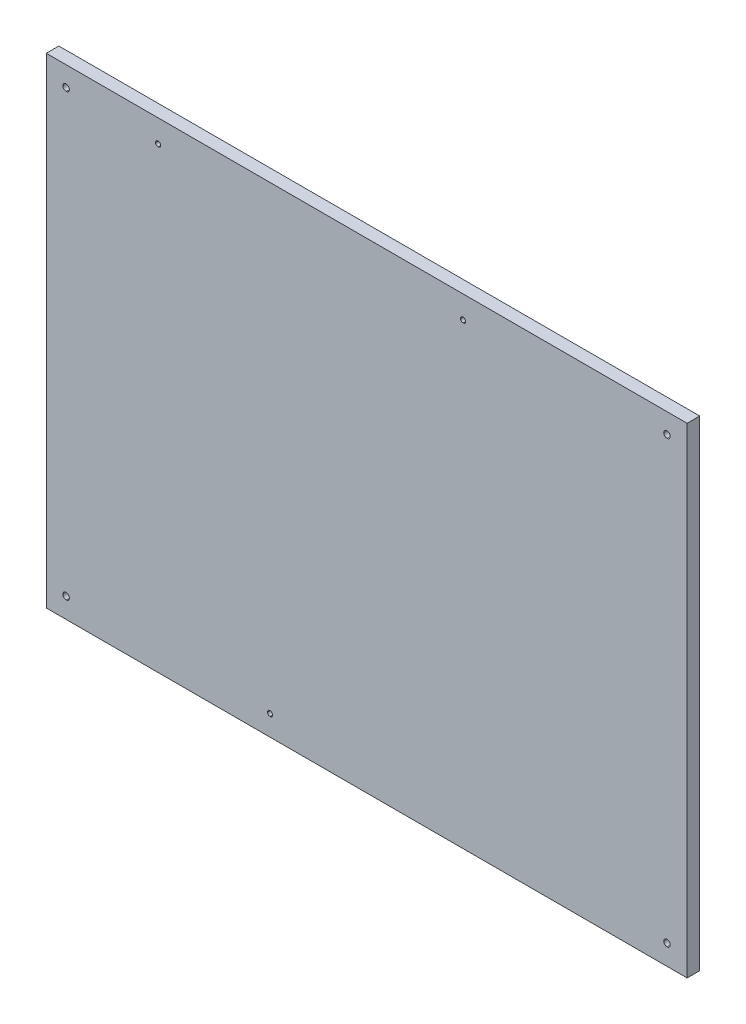
SolidWorks part; units mm, degrees
ref_plane "Front Plane" through (0, 0, 0) normal (0, 0, 1) x (1, 0, 0)
ref_plane "Top Plane" through (0, 0, 0) normal (0, 1, 0) x (1, 0, 0)
ref_plane "Right Plane" through (0, 0, 0) normal (1, 0, 0) x (0, 0, -1)
sketch "Model" plane through (0, 0, 0) normal (0, 0, 1) x (1, 0, 0)
  line L202 (85.3017, 123.303) -> (87.3337, 123.303)
  line L203 (87.3337, 123.303) -> (87.3337, 125.335)
  line L204 (87.3337, 125.335) -> (85.3017, 125.335)
  line L205 (85.3017, 125.335) -> (85.3017, 123.303)
  line L225 (58.3777, 121.779) -> (138.3453, 121.779)
  line L226 (138.3453, 121.779) -> (138.3453, 181.723)
  line L227 (138.3453, 181.723) -> (58.3777, 181.723)
  line L228 (58.3777, 181.723) -> (58.3777, 121.779)
  line L1737 (85.0477, 123.049) -> (110.4053, 123.049)
  line L1738 (110.4053, 123.049) -> (110.4053, 125.589)
  line L1739 (110.4053, 125.589) -> (85.0477, 125.589)
  line L1740 (85.0477, 125.589) -> (85.0477, 123.049)
  line L1741 (87.5877, 125.589) -> (87.5877, 123.049)
  line L1742 (96.9857, 126.3087) -> (96.9857, 126.224)
  line L1743 (96.9857, 126.224) -> (97.0703, 126.097)
  line L1744 (97.0703, 126.097) -> (97.4513, 126.097)
  line L1745 (97.4513, 126.097) -> (97.536, 126.224)
  line L1746 (97.536, 126.224) -> (97.536, 126.732)
  line L1747 (98.298, 126.5204) -> (98.2133, 126.4357)
  line L1748 (98.2133, 126.4357) -> (97.917, 126.4357)
  line L1749 (97.917, 126.4357) -> (97.8323, 126.5204)
  line L1750 (97.8323, 126.5204) -> (97.8323, 126.605)
  line L1751 (97.8323, 126.605) -> (97.917, 126.732)
  line L1752 (97.917, 126.732) -> (98.2133, 126.732)
  line L1753 (98.2133, 126.732) -> (98.298, 126.605)
  line L1754 (98.298, 126.605) -> (98.298, 126.224)
  line L1755 (98.298, 126.224) -> (98.2133, 126.097)
  line L1756 (98.2133, 126.097) -> (97.917, 126.097)
  line L1889 (67.2677, 178.8444) -> (67.564, 178.8444)
  line L1890 (67.564, 178.8444) -> (67.564, 178.548)
  line L1891 (67.564, 178.548) -> (66.929, 178.548)
  line L1892 (66.929, 178.548) -> (66.6327, 178.8444)
  line L1893 (66.6327, 178.8444) -> (66.6327, 179.1407)
  line L1894 (66.6327, 179.1407) -> (66.929, 179.437)
  line L1895 (66.929, 179.437) -> (67.3947, 179.437)
  line L1896 (67.3947, 179.437) -> (67.564, 179.31)
  line L1897 (67.9027, 178.548) -> (67.9027, 179.437)
  line L1898 (67.9027, 179.437) -> (68.834, 178.548)
  line L1899 (68.834, 178.548) -> (68.834, 179.437)
  line L1900 (69.1727, 178.548) -> (69.1727, 179.437)
  line L1901 (69.1727, 179.437) -> (69.8077, 179.437)
  line L1902 (69.8077, 179.437) -> (70.104, 179.1407)
  line L1903 (70.104, 179.1407) -> (70.104, 178.8444)
  line L1904 (70.104, 178.8444) -> (69.8077, 178.548)
  line L1905 (69.8077, 178.548) -> (69.1727, 178.548)
  line L1906 (74.549, 181.0457) -> (74.8877, 181.342)
  line L1907 (74.8877, 181.342) -> (74.8877, 180.453)
  line L1908 (76.9197, 181.215) -> (77.089, 181.342)
  line L1909 (77.089, 181.342) -> (77.5547, 181.342)
  line L1910 (77.5547, 181.342) -> (77.724, 181.215)
  line L1911 (77.724, 181.215) -> (77.724, 181.0457)
  line L1912 (77.724, 181.0457) -> (77.5547, 180.9187)
  line L1913 (77.5547, 180.9187) -> (77.089, 180.9187)
  line L1914 (77.089, 180.9187) -> (76.9197, 180.7494)
  line L1915 (76.9197, 180.7494) -> (76.9197, 180.453)
  line L1916 (76.9197, 180.453) -> (77.724, 180.453)
  line L1917 (79.4597, 181.215) -> (79.629, 181.342)
  line L1918 (79.629, 181.342) -> (80.0947, 181.342)
  line L1919 (80.0947, 181.342) -> (80.264, 181.215)
  line L1920 (80.264, 181.215) -> (80.264, 181.0457)
  line L1921 (80.264, 181.0457) -> (80.0947, 180.9187)
  line L1922 (80.0947, 180.9187) -> (80.264, 180.7494)
  line L1923 (80.264, 180.7494) -> (80.264, 180.58)
  line L1924 (80.264, 180.58) -> (80.0947, 180.453)
  line L1925 (80.0947, 180.453) -> (79.629, 180.453)
  line L1926 (79.629, 180.453) -> (79.4597, 180.58)
  line L1927 (79.7983, 180.9187) -> (80.0947, 180.9187)
  line L1928 (82.804, 180.7494) -> (81.8727, 180.7494)
  line L1929 (81.8727, 180.7494) -> (82.5077, 181.342)
  line L1930 (82.5077, 181.342) -> (82.5077, 180.453)
  line L1931 (113.2417, 181.342) -> (112.4373, 181.342)
  line L1932 (112.4373, 181.342) -> (112.4373, 181.0457)
  line L1933 (112.4373, 181.0457) -> (113.0723, 181.0457)
  line L1934 (113.0723, 181.0457) -> (113.2417, 180.9187)
  line L1935 (113.2417, 180.9187) -> (113.2417, 180.58)
  line L1936 (113.2417, 180.58) -> (113.0723, 180.453)
  line L1937 (113.0723, 180.453) -> (112.6067, 180.453)
  line L1938 (112.6067, 180.453) -> (112.4373, 180.58)
  line L1939 (115.7817, 181.215) -> (115.6123, 181.342)
  line L1940 (115.6123, 181.342) -> (115.1467, 181.342)
  line L1941 (115.1467, 181.342) -> (114.9773, 181.215)
  line L1942 (114.9773, 181.215) -> (114.9773, 180.58)
  line L1943 (114.9773, 180.58) -> (115.1467, 180.453)
  line L1944 (115.1467, 180.453) -> (115.6123, 180.453)
  line L1945 (115.6123, 180.453) -> (115.7817, 180.58)
  line L1946 (115.7817, 180.58) -> (115.7817, 180.7494)
  line L1947 (115.7817, 180.7494) -> (115.6123, 180.9187)
  line L1948 (115.6123, 180.9187) -> (114.9773, 180.9187)
  line L1949 (117.5173, 181.342) -> (118.3217, 181.342)
  line L1950 (118.3217, 181.342) -> (118.3217, 181.215)
  line L1951 (118.3217, 181.215) -> (117.5173, 180.453)
  line L1952 (120.2267, 180.9187) -> (120.0573, 181.0457)
  line L1953 (120.0573, 181.0457) -> (120.0573, 181.215)
  line L1954 (120.0573, 181.215) -> (120.2267, 181.342)
  line L1955 (120.2267, 181.342) -> (120.6923, 181.342)
  line L1956 (120.6923, 181.342) -> (120.8617, 181.215)
  line L1957 (120.8617, 181.215) -> (120.8617, 181.0457)
  line L1958 (120.8617, 181.0457) -> (120.6923, 180.9187)
  line L1959 (120.6923, 180.9187) -> (120.2267, 180.9187)
  line L1960 (120.2267, 180.9187) -> (120.0573, 180.7494)
  line L1961 (120.0573, 180.7494) -> (120.0573, 180.58)
  line L1962 (120.0573, 180.58) -> (120.2267, 180.453)
  line L1963 (120.2267, 180.453) -> (120.6923, 180.453)
  line L1964 (120.6923, 180.453) -> (120.8617, 180.58)
  line L1965 (120.8617, 180.58) -> (120.8617, 180.7494)
  line L1966 (120.8617, 180.7494) -> (120.6923, 180.9187)
  line L1967 (105.3677, 178.8444) -> (105.664, 178.8444)
  line L1968 (105.664, 178.8444) -> (105.664, 178.548)
  line L1969 (105.664, 178.548) -> (105.029, 178.548)
  line L1970 (105.029, 178.548) -> (104.7327, 178.8444)
  line L1971 (104.7327, 178.8444) -> (104.7327, 179.1407)
  line L1972 (104.7327, 179.1407) -> (105.029, 179.437)
  line L1973 (105.029, 179.437) -> (105.4947, 179.437)
  line L1974 (105.4947, 179.437) -> (105.664, 179.31)
  line L1975 (106.0027, 178.548) -> (106.0027, 179.437)
  line L1976 (106.0027, 179.437) -> (106.934, 178.548)
  line L1977 (106.934, 178.548) -> (106.934, 179.437)
  line L1978 (107.2727, 178.548) -> (107.2727, 179.437)
  line L1979 (107.2727, 179.437) -> (107.9077, 179.437)
  line L1980 (107.9077, 179.437) -> (108.204, 179.1407)
  line L1981 (108.204, 179.1407) -> (108.204, 178.8444)
  line L1982 (108.204, 178.8444) -> (107.9077, 178.548)
  line L1983 (107.9077, 178.548) -> (107.2727, 178.548)
  line L1984 (80.6027, 124.446) -> (81.534, 124.446)
  line L1985 (81.0683, 124.7424) -> (81.0683, 124.1074)
  line L1986 (82.169, 124.446) -> (81.9997, 124.573)
  line L1987 (81.9997, 124.573) -> (81.9997, 124.7424)
  line L1988 (81.9997, 124.7424) -> (82.169, 124.8694)
  line L1989 (82.169, 124.8694) -> (82.6347, 124.8694)
  line L1990 (82.6347, 124.8694) -> (82.804, 124.7424)
  line L1991 (82.804, 124.7424) -> (82.804, 124.573)
  line L1992 (82.804, 124.573) -> (82.6347, 124.446)
  line L1993 (82.6347, 124.446) -> (82.169, 124.446)
  line L1994 (82.169, 124.446) -> (81.9997, 124.2767)
  line L1995 (81.9997, 124.2767) -> (81.9997, 124.1074)
  line L1996 (81.9997, 124.1074) -> (82.169, 123.9804)
  line L1997 (82.169, 123.9804) -> (82.6347, 123.9804)
  line L1998 (82.6347, 123.9804) -> (82.804, 124.1074)
  line L1999 (82.804, 124.1074) -> (82.804, 124.2767)
  line L2000 (82.804, 124.2767) -> (82.6347, 124.446)
  line L2001 (83.1427, 124.573) -> (83.6083, 123.9804)
  line L2002 (83.6083, 123.9804) -> (84.074, 124.573)
  line L2003 (111.6753, 124.2767) -> (111.9717, 124.2767)
  line L2004 (111.9717, 124.2767) -> (111.9717, 123.9804)
  line L2005 (111.9717, 123.9804) -> (111.3367, 123.9804)
  line L2006 (111.3367, 123.9804) -> (111.0403, 124.2767)
  line L2007 (111.0403, 124.2767) -> (111.0403, 124.573)
  line L2008 (111.0403, 124.573) -> (111.3367, 124.8694)
  line L2009 (111.3367, 124.8694) -> (111.8023, 124.8694)
  line L2010 (111.8023, 124.8694) -> (111.9717, 124.7424)
  line L2011 (112.3103, 123.9804) -> (112.3103, 124.8694)
  line L2012 (112.3103, 124.8694) -> (113.2417, 123.9804)
  line L2013 (113.2417, 123.9804) -> (113.2417, 124.8694)
  line L2014 (113.5803, 123.9804) -> (113.5803, 124.8694)
  line L2015 (113.5803, 124.8694) -> (114.2153, 124.8694)
  line L2016 (114.2153, 124.8694) -> (114.5117, 124.573)
  line L2017 (114.5117, 124.573) -> (114.5117, 124.2767)
  line L2018 (114.5117, 124.2767) -> (114.2153, 123.9804)
  line L2019 (114.2153, 123.9804) -> (113.5803, 123.9804)
  circle A0 centre (86.2965, 124.3402) radius 0.3182
  circle A1 centre (72.3265, 178.9079) radius 0.3182
  circle A2 centre (110.3842, 178.9079) radius 0.3182
  spline S1168 degree 3 poles (86.614, 124.319) (86.614, 124.4884) (86.487, 124.6577) (86.3177, 124.6577) knots 0 0 0 0 1 1 1 1
  spline S1169 degree 3 poles (86.3177, 124.6577) (86.106, 124.6577) (85.979, 124.4884) (85.979, 124.319) knots 0 0 0 0 1 1 1 1
  spline S1170 degree 3 poles (85.979, 124.319) (85.979, 124.1497) (86.106, 124.0227) (86.3177, 124.0227) knots 0 0 0 0 1 1 1 1
  spline S1171 degree 3 poles (86.3177, 124.0227) (86.487, 124.0227) (86.614, 124.1497) (86.614, 124.319) knots 0 0 0 0 1 1 1 1
  spline S1172 degree 3 poles (89.8737, 124.319) (89.8737, 124.9117) (89.408, 125.3774) (88.8577, 125.3774) knots 0 0 0 0 1 1 1 1
  spline S1173 degree 3 poles (88.8577, 125.3774) (88.265, 125.3774) (87.7993, 124.9117) (87.7993, 124.319) knots 0 0 0 0 1 1 1 1
  spline S1174 degree 3 poles (87.7993, 124.319) (87.7993, 123.7687) (88.265, 123.303) (88.8577, 123.303) knots 0 0 0 0 1 1 1 1
  spline S1175 degree 3 poles (88.8577, 123.303) (89.408, 123.303) (89.8737, 123.7687) (89.8737, 124.319) knots 0 0 0 0 1 1 1 1
  spline S1176 degree 3 poles (89.154, 124.319) (89.154, 124.4884) (89.027, 124.6577) (88.8577, 124.6577) knots 0 0 0 0 1 1 1 1
  spline S1177 degree 3 poles (88.8577, 124.6577) (88.646, 124.6577) (88.519, 124.4884) (88.519, 124.319) knots 0 0 0 0 1 1 1 1
  spline S1178 degree 3 poles (88.519, 124.319) (88.519, 124.1497) (88.646, 124.0227) (88.8577, 124.0227) knots 0 0 0 0 1 1 1 1
  spline S1179 degree 3 poles (88.8577, 124.0227) (89.027, 124.0227) (89.154, 124.1497) (89.154, 124.319) knots 0 0 0 0 1 1 1 1
  spline S1180 degree 3 poles (92.4137, 124.319) (92.4137, 124.9117) (91.948, 125.3774) (91.3977, 125.3774) knots 0 0 0 0 1 1 1 1
  spline S1181 degree 3 poles (91.3977, 125.3774) (90.805, 125.3774) (90.3393, 124.9117) (90.3393, 124.319) knots 0 0 0 0 1 1 1 1
  spline S1182 degree 3 poles (90.3393, 124.319) (90.3393, 123.7687) (90.805, 123.303) (91.3977, 123.303) knots 0 0 0 0 1 1 1 1
  spline S1183 degree 3 poles (91.3977, 123.303) (91.948, 123.303) (92.4137, 123.7687) (92.4137, 124.319) knots 0 0 0 0 1 1 1 1
  spline S1184 degree 3 poles (91.694, 124.319) (91.694, 124.4884) (91.567, 124.6577) (91.3977, 124.6577) knots 0 0 0 0 1 1 1 1
  spline S1185 degree 3 poles (91.3977, 124.6577) (91.186, 124.6577) (91.059, 124.4884) (91.059, 124.319) knots 0 0 0 0 1 1 1 1
  spline S1186 degree 3 poles (91.059, 124.319) (91.059, 124.1497) (91.186, 124.0227) (91.3977, 124.0227) knots 0 0 0 0 1 1 1 1
  spline S1187 degree 3 poles (91.3977, 124.0227) (91.567, 124.0227) (91.694, 124.1497) (91.694, 124.319) knots 0 0 0 0 1 1 1 1
  spline S1188 degree 3 poles (94.9537, 124.319) (94.9537, 124.9117) (94.488, 125.3774) (93.9377, 125.3774) knots 0 0 0 0 1 1 1 1
  spline S1189 degree 3 poles (93.9377, 125.3774) (93.345, 125.3774) (92.8793, 124.9117) (92.8793, 124.319) knots 0 0 0 0 1 1 1 1
  spline S1190 degree 3 poles (92.8793, 124.319) (92.8793, 123.7687) (93.345, 123.303) (93.9377, 123.303) knots 0 0 0 0 1 1 1 1
  spline S1191 degree 3 poles (93.9377, 123.303) (94.488, 123.303) (94.9537, 123.7687) (94.9537, 124.319) knots 0 0 0 0 1 1 1 1
  spline S1192 degree 3 poles (94.234, 124.319) (94.234, 124.4884) (94.107, 124.6577) (93.9377, 124.6577) knots 0 0 0 0 1 1 1 1
  spline S1193 degree 3 poles (93.9377, 124.6577) (93.726, 124.6577) (93.599, 124.4884) (93.599, 124.319) knots 0 0 0 0 1 1 1 1
  spline S1194 degree 3 poles (93.599, 124.319) (93.599, 124.1497) (93.726, 124.0227) (93.9377, 124.0227) knots 0 0 0 0 1 1 1 1
  spline S1195 degree 3 poles (93.9377, 124.0227) (94.107, 124.0227) (94.234, 124.1497) (94.234, 124.319) knots 0 0 0 0 1 1 1 1
  spline S1196 degree 3 poles (97.4937, 124.319) (97.4937, 124.9117) (97.028, 125.3774) (96.4777, 125.3774) knots 0 0 0 0 1 1 1 1
  spline S1197 degree 3 poles (96.4777, 125.3774) (95.885, 125.3774) (95.4193, 124.9117) (95.4193, 124.319) knots 0 0 0 0 1 1 1 1
  spline S1198 degree 3 poles (95.4193, 124.319) (95.4193, 123.7687) (95.885, 123.303) (96.4777, 123.303) knots 0 0 0 0 1 1 1 1
  spline S1199 degree 3 poles (96.4777, 123.303) (97.028, 123.303) (97.4937, 123.7687) (97.4937, 124.319) knots 0 0 0 0 1 1 1 1
  spline S1200 degree 3 poles (96.774, 124.319) (96.774, 124.4884) (96.647, 124.6577) (96.4777, 124.6577) knots 0 0 0 0 1 1 1 1
  spline S1201 degree 3 poles (96.4777, 124.6577) (96.266, 124.6577) (96.139, 124.4884) (96.139, 124.319) knots 0 0 0 0 1 1 1 1
  spline S1202 degree 3 poles (96.139, 124.319) (96.139, 124.1497) (96.266, 124.0227) (96.4777, 124.0227) knots 0 0 0 0 1 1 1 1
  spline S1203 degree 3 poles (96.4777, 124.0227) (96.647, 124.0227) (96.774, 124.1497) (96.774, 124.319) knots 0 0 0 0 1 1 1 1
  spline S1204 degree 3 poles (100.0337, 124.319) (100.0337, 124.9117) (99.568, 125.3774) (99.0177, 125.3774) knots 0 0 0 0 1 1 1 1
  spline S1205 degree 3 poles (99.0177, 125.3774) (98.425, 125.3774) (97.9593, 124.9117) (97.9593, 124.319) knots 0 0 0 0 1 1 1 1
  spline S1206 degree 3 poles (97.9593, 124.319) (97.9593, 123.7687) (98.425, 123.303) (99.0177, 123.303) knots 0 0 0 0 1 1 1 1
  spline S1207 degree 3 poles (99.0177, 123.303) (99.568, 123.303) (100.0337, 123.7687) (100.0337, 124.319) knots 0 0 0 0 1 1 1 1
  spline S1208 degree 3 poles (99.314, 124.319) (99.314, 124.4884) (99.187, 124.6577) (99.0177, 124.6577) knots 0 0 0 0 1 1 1 1
  spline S1209 degree 3 poles (99.0177, 124.6577) (98.806, 124.6577) (98.679, 124.4884) (98.679, 124.319) knots 0 0 0 0 1 1 1 1
  spline S1210 degree 3 poles (98.679, 124.319) (98.679, 124.1497) (98.806, 124.0227) (99.0177, 124.0227) knots 0 0 0 0 1 1 1 1
  spline S1211 degree 3 poles (99.0177, 124.0227) (99.187, 124.0227) (99.314, 124.1497) (99.314, 124.319) knots 0 0 0 0 1 1 1 1
  spline S1212 degree 3 poles (102.5737, 124.319) (102.5737, 124.9117) (102.108, 125.3774) (101.5577, 125.3774) knots 0 0 0 0 1 1 1 1
  spline S1213 degree 3 poles (101.5577, 125.3774) (100.965, 125.3774) (100.4993, 124.9117) (100.4993, 124.319) knots 0 0 0 0 1 1 1 1
  spline S1214 degree 3 poles (100.4993, 124.319) (100.4993, 123.7687) (100.965, 123.303) (101.5577, 123.303) knots 0 0 0 0 1 1 1 1
  spline S1215 degree 3 poles (101.5577, 123.303) (102.108, 123.303) (102.5737, 123.7687) (102.5737, 124.319) knots 0 0 0 0 1 1 1 1
  spline S1216 degree 3 poles (101.854, 124.319) (101.854, 124.4884) (101.727, 124.6577) (101.5577, 124.6577) knots 0 0 0 0 1 1 1 1
  spline S1217 degree 3 poles (101.5577, 124.6577) (101.346, 124.6577) (101.219, 124.4884) (101.219, 124.319) knots 0 0 0 0 1 1 1 1
  spline S1218 degree 3 poles (101.219, 124.319) (101.219, 124.1497) (101.346, 124.0227) (101.5577, 124.0227) knots 0 0 0 0 1 1 1 1
  spline S1219 degree 3 poles (101.5577, 124.0227) (101.727, 124.0227) (101.854, 124.1497) (101.854, 124.319) knots 0 0 0 0 1 1 1 1
  spline S1220 degree 3 poles (105.1137, 124.319) (105.1137, 124.9117) (104.648, 125.3774) (104.0977, 125.3774) knots 0 0 0 0 1 1 1 1
  spline S1221 degree 3 poles (104.0977, 125.3774) (103.505, 125.3774) (103.0393, 124.9117) (103.0393, 124.319) knots 0 0 0 0 1 1 1 1
  spline S1222 degree 3 poles (103.0393, 124.319) (103.0393, 123.7687) (103.505, 123.303) (104.0977, 123.303) knots 0 0 0 0 1 1 1 1
  spline S1223 degree 3 poles (104.0977, 123.303) (104.648, 123.303) (105.1137, 123.7687) (105.1137, 124.319) knots 0 0 0 0 1 1 1 1
  spline S1224 degree 3 poles (104.394, 124.319) (104.394, 124.4884) (104.267, 124.6577) (104.0977, 124.6577) knots 0 0 0 0 1 1 1 1
  spline S1225 degree 3 poles (104.0977, 124.6577) (103.886, 124.6577) (103.759, 124.4884) (103.759, 124.319) knots 0 0 0 0 1 1 1 1
  spline S1226 degree 3 poles (103.759, 124.319) (103.759, 124.1497) (103.886, 124.0227) (104.0977, 124.0227) knots 0 0 0 0 1 1 1 1
  spline S1227 degree 3 poles (104.0977, 124.0227) (104.267, 124.0227) (104.394, 124.1497) (104.394, 124.319) knots 0 0 0 0 1 1 1 1
  spline S1228 degree 3 poles (107.6113, 124.319) (107.6113, 124.9117) (107.1457, 125.3774) (106.5953, 125.3774) knots 0 0 0 0 1 1 1 1
  spline S1229 degree 3 poles (106.5953, 125.3774) (106.0027, 125.3774) (105.537, 124.9117) (105.537, 124.319) knots 0 0 0 0 1 1 1 1
  spline S1230 degree 3 poles (105.537, 124.319) (105.537, 123.7687) (106.0027, 123.303) (106.5953, 123.303) knots 0 0 0 0 1 1 1 1
  spline S1231 degree 3 poles (106.5953, 123.303) (107.1457, 123.303) (107.6113, 123.7687) (107.6113, 124.319) knots 0 0 0 0 1 1 1 1
  spline S1232 degree 3 poles (106.8917, 124.319) (106.8917, 124.4884) (106.7647, 124.6577) (106.5953, 124.6577) knots 0 0 0 0 1 1 1 1
  spline S1233 degree 3 poles (106.5953, 124.6577) (106.3837, 124.6577) (106.2567, 124.4884) (106.2567, 124.319) knots 0 0 0 0 1 1 1 1
  spline S1234 degree 3 poles (106.2567, 124.319) (106.2567, 124.1497) (106.3837, 124.0227) (106.5953, 124.0227) knots 0 0 0 0 1 1 1 1
  spline S1235 degree 3 poles (106.5953, 124.0227) (106.7647, 124.0227) (106.8917, 124.1497) (106.8917, 124.319) knots 0 0 0 0 1 1 1 1
  spline S1236 degree 3 poles (110.1513, 124.319) (110.1513, 124.9117) (109.6857, 125.3774) (109.1353, 125.3774) knots 0 0 0 0 1 1 1 1
  spline S1237 degree 3 poles (109.1353, 125.3774) (108.5427, 125.3774) (108.077, 124.9117) (108.077, 124.319) knots 0 0 0 0 1 1 1 1
  spline S1238 degree 3 poles (108.077, 124.319) (108.077, 123.7687) (108.5427, 123.303) (109.1353, 123.303) knots 0 0 0 0 1 1 1 1
  spline S1239 degree 3 poles (109.1353, 123.303) (109.6857, 123.303) (110.1513, 123.7687) (110.1513, 124.319) knots 0 0 0 0 1 1 1 1
  spline S1240 degree 3 poles (109.4317, 124.319) (109.4317, 124.4884) (109.3047, 124.6577) (109.1353, 124.6577) knots 0 0 0 0 1 1 1 1
  spline S1241 degree 3 poles (109.1353, 124.6577) (108.9237, 124.6577) (108.7967, 124.4884) (108.7967, 124.319) knots 0 0 0 0 1 1 1 1
  spline S1242 degree 3 poles (108.7967, 124.319) (108.7967, 124.1497) (108.9237, 124.0227) (109.1353, 124.0227) knots 0 0 0 0 1 1 1 1
  spline S1243 degree 3 poles (109.1353, 124.0227) (109.3047, 124.0227) (109.4317, 124.1497) (109.4317, 124.319) knots 0 0 0 0 1 1 1 1
  spline S1244 degree 3 poles (62.7803, 124.2767) (62.7803, 125.335) (61.9337, 126.224) (60.8753, 126.224) knots 0 0 0 0 1 1 1 1
  spline S1245 degree 3 poles (60.8753, 126.224) (59.817, 126.224) (58.928, 125.335) (58.928, 124.2767) knots 0 0 0 0 1 1 1 1
  spline S1246 degree 3 poles (58.928, 124.2767) (58.928, 123.2607) (59.817, 122.3717) (60.8753, 122.3717) knots 0 0 0 0 1 1 1 1
  spline S1247 degree 3 poles (60.8753, 122.3717) (61.9337, 122.3717) (62.7803, 123.2607) (62.7803, 124.2767) knots 0 0 0 0 1 1 1 1
  spline S1248 degree 3 poles (61.2563, 124.2767) (61.2563, 124.5307) (61.087, 124.7) (60.8753, 124.7) knots 0 0 0 0 1 1 1 1
  spline S1249 degree 3 poles (60.8753, 124.7) (60.6213, 124.7) (60.452, 124.5307) (60.452, 124.2767) knots 0 0 0 0 1 1 1 1
  spline S1250 degree 3 poles (60.452, 124.2767) (60.452, 124.065) (60.6213, 123.8957) (60.8753, 123.8957) knots 0 0 0 0 1 1 1 1
  spline S1251 degree 3 poles (60.8753, 123.8957) (61.087, 123.8957) (61.2563, 124.065) (61.2563, 124.2767) knots 0 0 0 0 1 1 1 1
  spline S1252 degree 3 poles (137.7527, 124.2767) (137.7527, 125.335) (136.906, 126.224) (135.8477, 126.224) knots 0 0 0 0 1 1 1 1
  spline S1253 degree 3 poles (135.8477, 126.224) (134.7893, 126.224) (133.9003, 125.335) (133.9003, 124.2767) knots 0 0 0 0 1 1 1 1
  spline S1254 degree 3 poles (133.9003, 124.2767) (133.9003, 123.2607) (134.7893, 122.3717) (135.8477, 122.3717) knots 0 0 0 0 1 1 1 1
  spline S1255 degree 3 poles (135.8477, 122.3717) (136.906, 122.3717) (137.7527, 123.2607) (137.7527, 124.2767) knots 0 0 0 0 1 1 1 1
  spline S1256 degree 3 poles (136.2287, 124.2767) (136.2287, 124.5307) (136.0593, 124.7) (135.8477, 124.7) knots 0 0 0 0 1 1 1 1
  spline S1257 degree 3 poles (135.8477, 124.7) (135.5937, 124.7) (135.4243, 124.5307) (135.4243, 124.2767) knots 0 0 0 0 1 1 1 1
  spline S1258 degree 3 poles (135.4243, 124.2767) (135.4243, 124.065) (135.5937, 123.8957) (135.8477, 123.8957) knots 0 0 0 0 1 1 1 1
  spline S1259 degree 3 poles (135.8477, 123.8957) (136.0593, 123.8957) (136.2287, 124.065) (136.2287, 124.2767) knots 0 0 0 0 1 1 1 1
  spline S1260 degree 3 poles (137.7527, 179.2254) (137.7527, 180.2837) (136.906, 181.1727) (135.8477, 181.1727) knots 0 0 0 0 1 1 1 1
  spline S1261 degree 3 poles (135.8477, 181.1727) (134.7893, 181.1727) (133.9003, 180.2837) (133.9003, 179.2254) knots 0 0 0 0 1 1 1 1
  spline S1262 degree 3 poles (133.9003, 179.2254) (133.9003, 178.2094) (134.7893, 177.3204) (135.8477, 177.3204) knots 0 0 0 0 1 1 1 1
  spline S1263 degree 3 poles (135.8477, 177.3204) (136.906, 177.3204) (137.7527, 178.2094) (137.7527, 179.2254) knots 0 0 0 0 1 1 1 1
  spline S1264 degree 3 poles (136.2287, 179.2254) (136.2287, 179.4794) (136.0593, 179.6487) (135.8477, 179.6487) knots 0 0 0 0 1 1 1 1
  spline S1265 degree 3 poles (135.8477, 179.6487) (135.5937, 179.6487) (135.4243, 179.4794) (135.4243, 179.2254) knots 0 0 0 0 1 1 1 1
  spline S1266 degree 3 poles (135.4243, 179.2254) (135.4243, 179.0137) (135.5937, 178.8444) (135.8477, 178.8444) knots 0 0 0 0 1 1 1 1
  spline S1267 degree 3 poles (135.8477, 178.8444) (136.0593, 178.8444) (136.2287, 179.0137) (136.2287, 179.2254) knots 0 0 0 0 1 1 1 1
  spline S1268 degree 3 poles (75.9037, 178.8867) (75.9037, 179.4794) (75.438, 179.945) (74.8877, 179.945) knots 0 0 0 0 1 1 1 1
  spline S1269 degree 3 poles (74.8877, 179.945) (74.295, 179.945) (73.8293, 179.4794) (73.8293, 178.8867) knots 0 0 0 0 1 1 1 1
  spline S1270 degree 3 poles (73.8293, 178.8867) (73.8293, 178.3364) (74.295, 177.8707) (74.8877, 177.8707) knots 0 0 0 0 1 1 1 1
  spline S1271 degree 3 poles (74.8877, 177.8707) (75.438, 177.8707) (75.9037, 178.3364) (75.9037, 178.8867) knots 0 0 0 0 1 1 1 1
  spline S1272 degree 3 poles (75.184, 178.8867) (75.184, 179.056) (75.057, 179.2254) (74.8877, 179.2254) knots 0 0 0 0 1 1 1 1
  spline S1273 degree 3 poles (74.8877, 179.2254) (74.676, 179.2254) (74.549, 179.056) (74.549, 178.8867) knots 0 0 0 0 1 1 1 1
  spline S1274 degree 3 poles (74.549, 178.8867) (74.549, 178.7174) (74.676, 178.5904) (74.8877, 178.5904) knots 0 0 0 0 1 1 1 1
  spline S1275 degree 3 poles (74.8877, 178.5904) (75.057, 178.5904) (75.184, 178.7174) (75.184, 178.8867) knots 0 0 0 0 1 1 1 1
  spline S1276 degree 3 poles (78.4437, 178.8867) (78.4437, 179.4794) (77.978, 179.945) (77.4277, 179.945) knots 0 0 0 0 1 1 1 1
  spline S1277 degree 3 poles (77.4277, 179.945) (76.835, 179.945) (76.3693, 179.4794) (76.3693, 178.8867) knots 0 0 0 0 1 1 1 1
  spline S1278 degree 3 poles (76.3693, 178.8867) (76.3693, 178.3364) (76.835, 177.8707) (77.4277, 177.8707) knots 0 0 0 0 1 1 1 1
  spline S1279 degree 3 poles (77.4277, 177.8707) (77.978, 177.8707) (78.4437, 178.3364) (78.4437, 178.8867) knots 0 0 0 0 1 1 1 1
  spline S1280 degree 3 poles (77.724, 178.8867) (77.724, 179.056) (77.597, 179.2254) (77.4277, 179.2254) knots 0 0 0 0 1 1 1 1
  spline S1281 degree 3 poles (77.4277, 179.2254) (77.216, 179.2254) (77.089, 179.056) (77.089, 178.8867) knots 0 0 0 0 1 1 1 1
  spline S1282 degree 3 poles (77.089, 178.8867) (77.089, 178.7174) (77.216, 178.5904) (77.4277, 178.5904) knots 0 0 0 0 1 1 1 1
  spline S1283 degree 3 poles (77.4277, 178.5904) (77.597, 178.5904) (77.724, 178.7174) (77.724, 178.8867) knots 0 0 0 0 1 1 1 1
  spline S1284 degree 3 poles (80.9837, 178.8867) (80.9837, 179.4794) (80.518, 179.945) (79.9677, 179.945) knots 0 0 0 0 1 1 1 1
  spline S1285 degree 3 poles (79.9677, 179.945) (79.375, 179.945) (78.9093, 179.4794) (78.9093, 178.8867) knots 0 0 0 0 1 1 1 1
  spline S1286 degree 3 poles (78.9093, 178.8867) (78.9093, 178.3364) (79.375, 177.8707) (79.9677, 177.8707) knots 0 0 0 0 1 1 1 1
  spline S1287 degree 3 poles (79.9677, 177.8707) (80.518, 177.8707) (80.9837, 178.3364) (80.9837, 178.8867) knots 0 0 0 0 1 1 1 1
  spline S1288 degree 3 poles (80.264, 178.8867) (80.264, 179.056) (80.137, 179.2254) (79.9677, 179.2254) knots 0 0 0 0 1 1 1 1
  spline S1289 degree 3 poles (79.9677, 179.2254) (79.756, 179.2254) (79.629, 179.056) (79.629, 178.8867) knots 0 0 0 0 1 1 1 1
  spline S1290 degree 3 poles (79.629, 178.8867) (79.629, 178.7174) (79.756, 178.5904) (79.9677, 178.5904) knots 0 0 0 0 1 1 1 1
  spline S1291 degree 3 poles (79.9677, 178.5904) (80.137, 178.5904) (80.264, 178.7174) (80.264, 178.8867) knots 0 0 0 0 1 1 1 1
  spline S1292 degree 3 poles (83.5237, 178.8867) (83.5237, 179.4794) (83.058, 179.945) (82.5077, 179.945) knots 0 0 0 0 1 1 1 1
  spline S1293 degree 3 poles (82.5077, 179.945) (81.915, 179.945) (81.4493, 179.4794) (81.4493, 178.8867) knots 0 0 0 0 1 1 1 1
  spline S1294 degree 3 poles (81.4493, 178.8867) (81.4493, 178.3364) (81.915, 177.8707) (82.5077, 177.8707) knots 0 0 0 0 1 1 1 1
  spline S1295 degree 3 poles (82.5077, 177.8707) (83.058, 177.8707) (83.5237, 178.3364) (83.5237, 178.8867) knots 0 0 0 0 1 1 1 1
  spline S1296 degree 3 poles (82.804, 178.8867) (82.804, 179.056) (82.677, 179.2254) (82.5077, 179.2254) knots 0 0 0 0 1 1 1 1
  spline S1297 degree 3 poles (82.5077, 179.2254) (82.296, 179.2254) (82.169, 179.056) (82.169, 178.8867) knots 0 0 0 0 1 1 1 1
  spline S1298 degree 3 poles (82.169, 178.8867) (82.169, 178.7174) (82.296, 178.5904) (82.5077, 178.5904) knots 0 0 0 0 1 1 1 1
  spline S1299 degree 3 poles (82.5077, 178.5904) (82.677, 178.5904) (82.804, 178.7174) (82.804, 178.8867) knots 0 0 0 0 1 1 1 1
  spline S1300 degree 3 poles (113.9613, 178.8867) (113.9613, 179.4794) (113.4957, 179.945) (112.9453, 179.945) knots 0 0 0 0 1 1 1 1
  spline S1301 degree 3 poles (112.9453, 179.945) (112.3527, 179.945) (111.887, 179.4794) (111.887, 178.8867) knots 0 0 0 0 1 1 1 1
  spline S1302 degree 3 poles (111.887, 178.8867) (111.887, 178.3364) (112.3527, 177.8707) (112.9453, 177.8707) knots 0 0 0 0 1 1 1 1
  spline S1303 degree 3 poles (112.9453, 177.8707) (113.4957, 177.8707) (113.9613, 178.3364) (113.9613, 178.8867) knots 0 0 0 0 1 1 1 1
  spline S1304 degree 3 poles (113.2417, 178.8867) (113.2417, 179.056) (113.1147, 179.2254) (112.9453, 179.2254) knots 0 0 0 0 1 1 1 1
  spline S1305 degree 3 poles (112.9453, 179.2254) (112.7337, 179.2254) (112.6067, 179.056) (112.6067, 178.8867) knots 0 0 0 0 1 1 1 1
  spline S1306 degree 3 poles (112.6067, 178.8867) (112.6067, 178.7174) (112.7337, 178.5904) (112.9453, 178.5904) knots 0 0 0 0 1 1 1 1
  spline S1307 degree 3 poles (112.9453, 178.5904) (113.1147, 178.5904) (113.2417, 178.7174) (113.2417, 178.8867) knots 0 0 0 0 1 1 1 1
  spline S1308 degree 3 poles (116.5013, 178.8867) (116.5013, 179.4794) (116.0357, 179.945) (115.4853, 179.945) knots 0 0 0 0 1 1 1 1
  spline S1309 degree 3 poles (115.4853, 179.945) (114.8927, 179.945) (114.427, 179.4794) (114.427, 178.8867) knots 0 0 0 0 1 1 1 1
  spline S1310 degree 3 poles (114.427, 178.8867) (114.427, 178.3364) (114.8927, 177.8707) (115.4853, 177.8707) knots 0 0 0 0 1 1 1 1
  spline S1311 degree 3 poles (115.4853, 177.8707) (116.0357, 177.8707) (116.5013, 178.3364) (116.5013, 178.8867) knots 0 0 0 0 1 1 1 1
  spline S1312 degree 3 poles (115.7817, 178.8867) (115.7817, 179.056) (115.6547, 179.2254) (115.4853, 179.2254) knots 0 0 0 0 1 1 1 1
  spline S1313 degree 3 poles (115.4853, 179.2254) (115.2737, 179.2254) (115.1467, 179.056) (115.1467, 178.8867) knots 0 0 0 0 1 1 1 1
  spline S1314 degree 3 poles (115.1467, 178.8867) (115.1467, 178.7174) (115.2737, 178.5904) (115.4853, 178.5904) knots 0 0 0 0 1 1 1 1
  spline S1315 degree 3 poles (115.4853, 178.5904) (115.6547, 178.5904) (115.7817, 178.7174) (115.7817, 178.8867) knots 0 0 0 0 1 1 1 1
  spline S1316 degree 3 poles (119.0413, 178.8867) (119.0413, 179.4794) (118.5757, 179.945) (118.0253, 179.945) knots 0 0 0 0 1 1 1 1
  spline S1317 degree 3 poles (118.0253, 179.945) (117.4327, 179.945) (116.967, 179.4794) (116.967, 178.8867) knots 0 0 0 0 1 1 1 1
  spline S1318 degree 3 poles (116.967, 178.8867) (116.967, 178.3364) (117.4327, 177.8707) (118.0253, 177.8707) knots 0 0 0 0 1 1 1 1
  spline S1319 degree 3 poles (118.0253, 177.8707) (118.5757, 177.8707) (119.0413, 178.3364) (119.0413, 178.8867) knots 0 0 0 0 1 1 1 1
  spline S1320 degree 3 poles (118.3217, 178.8867) (118.3217, 179.056) (118.1947, 179.2254) (118.0253, 179.2254) knots 0 0 0 0 1 1 1 1
  spline S1321 degree 3 poles (118.0253, 179.2254) (117.8137, 179.2254) (117.6867, 179.056) (117.6867, 178.8867) knots 0 0 0 0 1 1 1 1
  spline S1322 degree 3 poles (117.6867, 178.8867) (117.6867, 178.7174) (117.8137, 178.5904) (118.0253, 178.5904) knots 0 0 0 0 1 1 1 1
  spline S1323 degree 3 poles (118.0253, 178.5904) (118.1947, 178.5904) (118.3217, 178.7174) (118.3217, 178.8867) knots 0 0 0 0 1 1 1 1
  spline S1324 degree 3 poles (121.5813, 178.8867) (121.5813, 179.4794) (121.1157, 179.945) (120.5653, 179.945) knots 0 0 0 0 1 1 1 1
  spline S1325 degree 3 poles (120.5653, 179.945) (119.9727, 179.945) (119.507, 179.4794) (119.507, 178.8867) knots 0 0 0 0 1 1 1 1
  spline S1326 degree 3 poles (119.507, 178.8867) (119.507, 178.3364) (119.9727, 177.8707) (120.5653, 177.8707) knots 0 0 0 0 1 1 1 1
  spline S1327 degree 3 poles (120.5653, 177.8707) (121.1157, 177.8707) (121.5813, 178.3364) (121.5813, 178.8867) knots 0 0 0 0 1 1 1 1
  spline S1328 degree 3 poles (120.8617, 178.8867) (120.8617, 179.056) (120.7347, 179.2254) (120.5653, 179.2254) knots 0 0 0 0 1 1 1 1
  spline S1329 degree 3 poles (120.5653, 179.2254) (120.3537, 179.2254) (120.2267, 179.056) (120.2267, 178.8867) knots 0 0 0 0 1 1 1 1
  spline S1330 degree 3 poles (120.2267, 178.8867) (120.2267, 178.7174) (120.3537, 178.5904) (120.5653, 178.5904) knots 0 0 0 0 1 1 1 1
  spline S1331 degree 3 poles (120.5653, 178.5904) (120.7347, 178.5904) (120.8617, 178.7174) (120.8617, 178.8867) knots 0 0 0 0 1 1 1 1
  spline S1332 degree 3 poles (73.3637, 178.8867) (73.3637, 179.4794) (72.898, 179.945) (72.3477, 179.945) knots 0 0 0 0 1 1 1 1
  spline S1333 degree 3 poles (72.3477, 179.945) (71.755, 179.945) (71.2893, 179.4794) (71.2893, 178.8867) knots 0 0 0 0 1 1 1 1
  spline S1334 degree 3 poles (71.2893, 178.8867) (71.2893, 178.3364) (71.755, 177.8707) (72.3477, 177.8707) knots 0 0 0 0 1 1 1 1
  spline S1335 degree 3 poles (72.3477, 177.8707) (72.898, 177.8707) (73.3637, 178.3364) (73.3637, 178.8867) knots 0 0 0 0 1 1 1 1
  spline S1336 degree 3 poles (72.644, 178.8867) (72.644, 179.056) (72.517, 179.2254) (72.3477, 179.2254) knots 0 0 0 0 1 1 1 1
  spline S1337 degree 3 poles (72.3477, 179.2254) (72.136, 179.2254) (72.009, 179.056) (72.009, 178.8867) knots 0 0 0 0 1 1 1 1
  spline S1338 degree 3 poles (72.009, 178.8867) (72.009, 178.7174) (72.136, 178.5904) (72.3477, 178.5904) knots 0 0 0 0 1 1 1 1
  spline S1339 degree 3 poles (72.3477, 178.5904) (72.517, 178.5904) (72.644, 178.7174) (72.644, 178.8867) knots 0 0 0 0 1 1 1 1
  spline S1372 degree 3 poles (111.4213, 178.8867) (111.4213, 179.4794) (110.9557, 179.945) (110.4053, 179.945) knots 0 0 0 0 1 1 1 1
  spline S1373 degree 3 poles (110.4053, 179.945) (109.8127, 179.945) (109.347, 179.4794) (109.347, 178.8867) knots 0 0 0 0 1 1 1 1
  spline S1374 degree 3 poles (109.347, 178.8867) (109.347, 178.3364) (109.8127, 177.8707) (110.4053, 177.8707) knots 0 0 0 0 1 1 1 1
  spline S1375 degree 3 poles (110.4053, 177.8707) (110.9557, 177.8707) (111.4213, 178.3364) (111.4213, 178.8867) knots 0 0 0 0 1 1 1 1
  spline S1376 degree 3 poles (110.7017, 178.8867) (110.7017, 179.056) (110.5747, 179.2254) (110.4053, 179.2254) knots 0 0 0 0 1 1 1 1
  spline S1377 degree 3 poles (110.4053, 179.2254) (110.1937, 179.2254) (110.0667, 179.056) (110.0667, 178.8867) knots 0 0 0 0 1 1 1 1
  spline S1378 degree 3 poles (110.0667, 178.8867) (110.0667, 178.7174) (110.1937, 178.5904) (110.4053, 178.5904) knots 0 0 0 0 1 1 1 1
  spline S1379 degree 3 poles (110.4053, 178.5904) (110.5747, 178.5904) (110.7017, 178.7174) (110.7017, 178.8867) knots 0 0 0 0 1 1 1 1
  spline S1380 degree 3 poles (62.7803, 179.2254) (62.7803, 180.2837) (61.9337, 181.1727) (60.8753, 181.1727) knots 0 0 0 0 1 1 1 1
  spline S1381 degree 3 poles (60.8753, 181.1727) (59.817, 181.1727) (58.928, 180.2837) (58.928, 179.2254) knots 0 0 0 0 1 1 1 1
  spline S1382 degree 3 poles (58.928, 179.2254) (58.928, 178.2094) (59.817, 177.3204) (60.8753, 177.3204) knots 0 0 0 0 1 1 1 1
  spline S1383 degree 3 poles (60.8753, 177.3204) (61.9337, 177.3204) (62.7803, 178.2094) (62.7803, 179.2254) knots 0 0 0 0 1 1 1 1
  spline S1384 degree 3 poles (61.2563, 179.2254) (61.2563, 179.4794) (61.087, 179.6487) (60.8753, 179.6487) knots 0 0 0 0 1 1 1 1
  spline S1385 degree 3 poles (60.8753, 179.6487) (60.6213, 179.6487) (60.452, 179.4794) (60.452, 179.2254) knots 0 0 0 0 1 1 1 1
  spline S1386 degree 3 poles (60.452, 179.2254) (60.452, 179.0137) (60.6213, 178.8444) (60.8753, 178.8444) knots 0 0 0 0 1 1 1 1
  spline S1387 degree 3 poles (60.8753, 178.8444) (61.087, 178.8444) (61.2563, 179.0137) (61.2563, 179.2254) knots 0 0 0 0 1 1 1 1
extrude "Boss-Extrude2" add sketch "Model" against normal blind 1.57 contours L227 L228 L225 L226 | S1251 S1248 S1249 S1250 | S1259 S1256 S1257 S1258 | S1267 S1264 S1265 S1266 | S1387 S1384 S1385 S1386 | S1336 S1337 S1338 S1339 | S1379 S1376 S1377 S1378 | S1171 S1168 S1169 S1170
